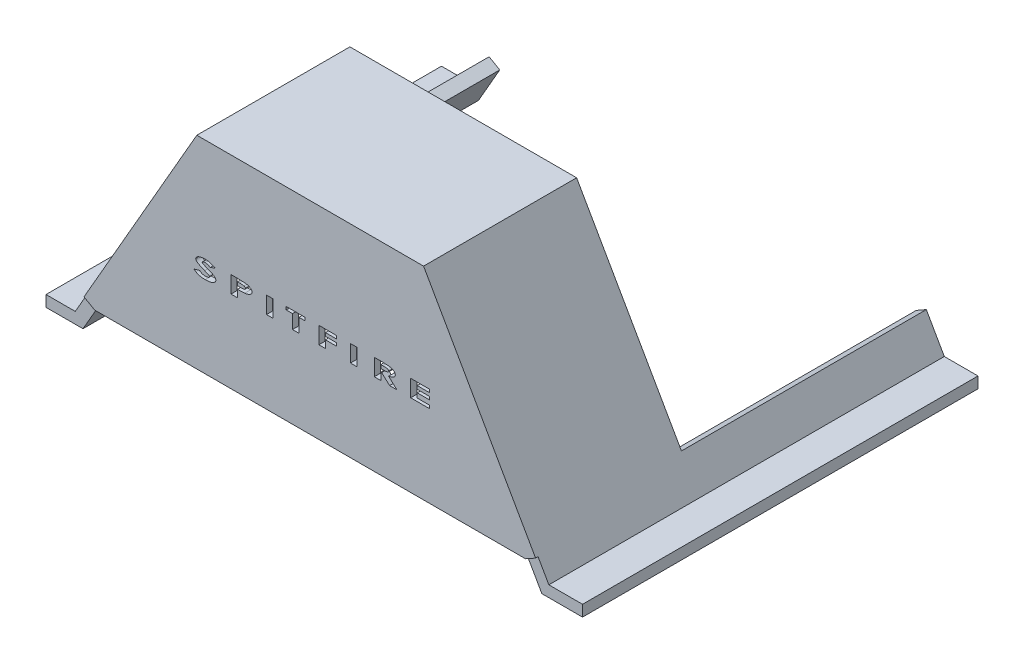
SolidWorks part; units mm, degrees
ref_plane "Front Plane" through (0, 0, 0) normal (0, 0, 1) x (1, 0, 0)
ref_plane "Top Plane" through (0, 0, 0) normal (0, 1, 0) x (1, 0, 0)
ref_plane "Right Plane" through (0, 0, 0) normal (1, 0, 0) x (0, 0, -1)
sketch "Sketch1" plane through (0, 0, 0) normal (0, 0, 1) x (1, 0, 0)
  line L0 (-44.8538, -1.5886) -> (-47.0562, -0.3232)
  line L1 (21.9172, 38.146) -> (-22.0768, 38.0539)
  line L2 (-22.0768, 38.0539) -> (-44.8538, -1.5886)
  line L7 (-32.9556, -19.1191) -> (-21.9172, -38.146) [skipped]
  line L8 (0.0798, -38.0999) -> (22.0768, -38.0539) [skipped]
  line L9 (33.0354, -18.9809) -> (43.994, 0.0921) [skipped]
  line L14 (-44.8538, -1.5886) -> (57.1508, -1.5886) construction
  line L15 (21.9172, 38.146) -> (44.5331, -1.5886)
  line L16 (43.994, 0.0921) -> (21.9172, 38.146) [skipped]
  line L17 (-47.0562, -0.3232) -> (-23.6464, 40.4204)
  line L18 (-23.6464, 40.4204) -> (23.3904, 40.4204)
  line L19 (23.3904, 40.4204) -> (46.6346, -0.4179)
  line L20 (46.6346, -0.4179) -> (44.5331, -1.5886)
  dimension "D1" = 46.99
  dimension "D2" = 46.99
  dimension "D3" = 2.54
  dimension "D4" = 45.72
  dimension "D5" = 45.72
  dimension "D6" = 89.387
extrude "Boss-Extrude1" add sketch "Sketch1" along normal blind 30.48
sketch "Sketch7" plane through (0, 0, 30.48) normal (0, 0, 1) x (1, 0, 0)
  line L0 (-23.6464, 40.4204) -> (-47.0562, -0.3232)
  line L1 (-47.0562, -0.3232) -> (-44.8538, -1.5886)
  line L2 (-44.8538, -1.5886) -> (44.5331, -1.5886)
  line L3 (44.5331, -1.5886) -> (46.6346, -0.4179)
  line L4 (46.6346, -0.4179) -> (23.3904, 40.4204)
  line L5 (23.3904, 40.4204) -> (-23.6464, 40.4204)
extrude "Boss-Extrude4" add sketch "Sketch7" along normal blind 1.27
sketch "Sketch8" plane through (0, 0, 0) normal (0, 0, -1) x (-1, 0, 0)
  line L0 (-43.0476, 1.0213) -> (-47.4227, -6.6653)
  line L1 (-21.9172, 38.146) -> (-44.5331, -1.5886) construction
  line L2 (-47.4227, -6.6653) -> (-55.8608, -6.6653)
  line L3 (-55.8608, -6.6653) -> (-55.8608, -4.3515)
  line L4 (-43.0476, 1.0213) -> (-45.1381, 2.2112)
  line L5 (-46.6346, -0.4179) -> (-23.3904, 40.4204) construction
  line L6 (-45.1381, 2.2112) -> (-48.8735, -4.3515)
  line L7 (-48.8735, -4.3515) -> (-55.8608, -4.3515)
  line L8 (43.3542, 1.0213) -> (47.7707, -6.6653)
  line L9 (44.8538, -1.5886) -> (22.0768, 38.0539) construction
  line L10 (47.7707, -6.6653) -> (55.4456, -6.6653)
  line L11 (55.4456, -6.6653) -> (55.4456, -4.3515)
  line L12 (43.3542, 1.0213) -> (45.5566, 2.2867)
  line L13 (23.6464, 40.4204) -> (47.0562, -0.3232) construction
  line L14 (45.5566, 2.2867) -> (49.3707, -4.3515)
  line L15 (49.3707, -4.3515) -> (55.4456, -4.3515)
extrude "Boss-Extrude5" add sketch "Sketch8" along normal blind 50.8 and the other way blind 31.242
sketch "Sketch9" plane through (0, 0, 31.75) normal (0, 0, 1) x (1, 0, 0)
  text T0 "<b>SPITFIRE</b>" font "Century Gothic" height 3.5
extrude "Cut-Extrude3" cut sketch "Sketch9" against normal blind 50.8
